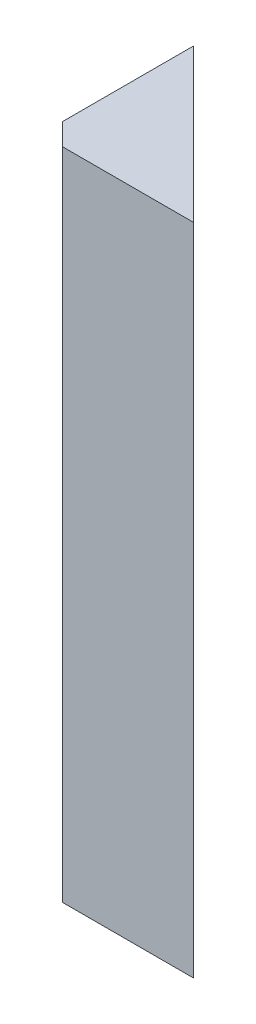
SolidWorks part; units mm, degrees
ref_plane "Front Plane" through (0, 0, 0) normal (0, 0, 1) x (1, 0, 0)
ref_plane "Top Plane" through (0, 0, 0) normal (0, 1, 0) x (1, 0, 0)
ref_plane "Right Plane" through (0, 0, 0) normal (1, 0, 0) x (0, 0, -1)
sketch "Sketch1" plane through (0, 0, 0) normal (0, 1, 0) x (1, 0, 0)
  line L0 (0, 0) -> (0, 0.3)
  line L1 (0, 0.15) -> (0.2, 0.15) construction
  line L2 (0.05, -0.05) -> (0.35, -0.05)
  line L3 (0, 0.3) -> (0.35, -0.05)
  line L4 (0, 0) -> (0.05, -0.05)
  circle A0 centre (0.2, 0.15) radius 0.2 construction
  point P8 (0.2, -0.05)
  dimension "D1" = 0.3
  dimension "D2" = 0.2
  dimension "D3" = 0.3
  dimension "D4" = 90
extrude "Boss-Extrude1" add sketch "Sketch1" along normal blind 1.5
equation "\"t\"= 0.3'thickness of the sheets"
equation "\"FlexJoint\"= 0.15'Width of flextures"
equation "\"FoldJoint\"= 0.4'Width of folding joints"
equation "\"AssembleAngle\"= 90'Angle of assembly parts"
equation "\"D1@Sketch1\"=\"t\""
equation "\"D2@Sketch1\"=\"FoldJoint\"/2"
equation "\"D3@Sketch1\"=\"t\""
equation "\"D4@Sketch1\"=\"AssembleAngle\""
